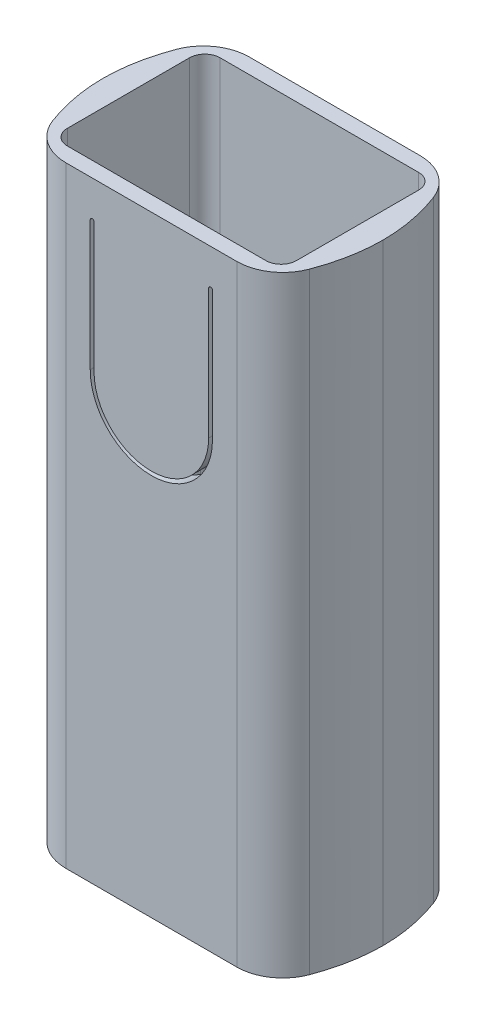
SolidWorks part; units mm, degrees
ref_plane "Front Plane" through (0, 0, 0) normal (0, 0, 1) x (1, 0, 0)
ref_plane "Top Plane" through (0, 0, 0) normal (0, 1, 0) x (1, 0, 0)
ref_plane "Right Plane" through (0, 0, 0) normal (1, 0, 0) x (0, 0, -1)
ref_plane "Plane1" through (0, 58, 0) normal (0, 1, 0) x (1, 0, 0)
sketch "Sketch8" plane through (0, 58, 0) normal (0, 1, 0) x (1, 0, 0)
  line L1 (-15, -8) -> (-15, 8)
  line L2 (-13, 10) -> (13, 10)
  line L5 (-15, 10) -> (-14.2911, 9.5274) construction
  line L8 (-11.1948, 12) -> (11.1948, 12)
  line L11 (-15.4079, 10.272) -> (-14.2911, 9.5274) construction
  line L12 (15.4079, 10.272) -> (14.2911, 9.5274) construction
  line L15 (0, 12) -> (0, -12) construction
  line L16 (15, 10) -> (14.2911, 9.5274) construction
  line L17 (15, -8) -> (15, 8)
  line L18 (15, -10) -> (14.2911, -9.5274) construction
  line L19 (15.4079, -10.272) -> (14.2911, -9.5274) construction
  line L20 (-18.3347, 0) -> (18.3347, 0) construction
  line L21 (0, 0) -> (0, 12) construction
  line L22 (-15.4079, -10.272) -> (-14.2911, -9.5274) construction
  line L23 (-15, -10) -> (-14.2911, -9.5274) construction
  line L24 (-11.1948, -12) -> (11.1948, -12)
  line L25 (-13, -10) -> (13, -10)
  arc A8 (-13, 10) -> (-15, 8) centre (-13, 8) ccw
  arc A10 (-11.1948, 12) -> (-16.8117, 8.1097) centre (-11.1948, 6) ccw
  arc A11 (11.1948, 12) -> (16.8117, 8.1097) centre (11.1948, 6) cw
  arc A12 (13, 10) -> (15, 8) centre (13, 8) cw
  arc A13 (13, -10) -> (15, -8) centre (13, -8) ccw
  arc A14 (11.1948, -12) -> (16.8117, -8.1097) centre (11.1948, -6) ccw
  arc A15 (-11.1948, -12) -> (-16.8117, -8.1097) centre (-11.1948, -6) cw
  arc A16 (-13, -10) -> (-15, -8) centre (-13, -8) cw
  spline S0 degree 3 poles (-18.3347, 0) (-18.3272, 2.7261) (-17.8195, 5.4265) (-16.8117, 8.1097) knots 0.502499 0.502499 0.502499 0.502499 0.837905 0.837905 0.837905 0.837905
  spline S1 degree 3 poles (18.3347, 0) (18.3272, 2.7261) (17.8195, 5.4265) (16.8117, 8.1097) knots 0.502499 0.502499 0.502499 0.502499 0.837905 0.837905 0.837905 0.837905
  spline S2 degree 3 poles (18.3347, 0) (18.3272, -2.7261) (17.8195, -5.4265) (16.8117, -8.1097) knots 0.502499 0.502499 0.502499 0.502499 0.837905 0.837905 0.837905 0.837905
  spline S3 degree 3 poles (-18.3347, 0) (-18.3272, -2.7261) (-17.8195, -5.4265) (-16.8117, -8.1097) knots 0.502499 0.502499 0.502499 0.502499 0.837905 0.837905 0.837905 0.837905
  point P0 (0, 0)
  point P4 (0, 0)
  point P5 (0, 0)
  point P8 (-15, 0)
  point P19 (-15, 10)
  point P26 (0, 0)
  point P27 (-12, 9.5)
  point P36 (0, 10)
  point P37 (12, 9.5)
  point P51 (-18.3347, 0)
  point P53 (-15, 0)
  point P55 (12, -9.5)
  point P61 (15, 0)
  point P62 (0, -10)
  point P63 (-12, -9.5)
  dimension "D3" = 8.2959
  dimension "D6" = 3.8903
  dimension "D2" = 6
  dimension "D7" = 2
  dimension "D1" = 13.9635
  dimension "D4" = 3.3347
  dimension "D5" = 1.523
  dimension "D8" = 2
  dimension "D9" = 15
sketch "Sketch11" plane through (0, 58, 0) normal (0, 1, 0) x (1, 0, 0)
  line L10 (-13, 10) -> (13, 10) construction
  line L11 (13, 10) -> (15, 10)
  line L13 (-13, 7.4379) -> (-13, 10)
  line L19 (15, 10) -> (15, 6.9379)
  line L20 (15, 6.9379) -> (13.5, 6.9379)
  line L21 (13, 7.4379) -> (13, 10)
  line L22 (-15, 6.9379) -> (-13.5, 6.9379)
  line L23 (-15, 10) -> (-15, 6.9379)
  line L24 (-13, 10) -> (-15, 10)
  arc A4 (13.5, 6.9379) -> (13, 7.4379) centre (13.5, 7.4379) cw
  arc A5 (-13.5, 6.9379) -> (-13, 7.4379) centre (-13.5, 7.4379) ccw
  point P14 (0, 0)
  dimension "D1" = 0.5
extrude "Boss-Extrude4" add sketch "Sketch8" along normal blind 80
extrude "Boss-Extrude5" add sketch "Sketch11" along normal blind 57
sketch "Sketch12" plane through (0, 0, 12) normal (0, 0, 1) x (1, 0, 0)
  line L1 (0, 116.1342) -> (0, 135.2209) construction
  line L2 (7.5, 133.1342) -> (7.5, 116.1342)
  line L3 (-7.5, 133.1342) -> (-7.5, 116.1342)
  line L4 (8, 133.1342) -> (8, 116.1342)
  line L5 (-8, 116.1342) -> (-8, 133.1342)
  line L6 (7.5, 130.5553) -> (0, 130.5553) construction
  line L7 (0, 130.5553) -> (-7.5, 130.5553) construction
  line L8 (-11.1948, 138) -> (11.1948, 138) construction
  line L9 (0, 138) -> (0, 58) construction
  line L10 (13.2, 58) -> (-13.2, 58) construction
  arc A1 (8, 116.1342) -> (-8, 116.1342) centre (0, 116.1342) cw
  arc A2 (7.5, 133.1342) -> (8, 133.1342) centre (7.75, 133.1342) cw
  arc A3 (-8, 133.1342) -> (-7.5, 133.1342) centre (-7.75, 133.1342) cw
  arc A4 (7.5, 116.1342) -> (-7.5, 116.1342) centre (0, 116.1342) cw
  point P1 (0, 108.6342)
  point P6 (0, 0)
  point P14 (0, 108.1342)
  point P20 (0.4953, 108.6342)
  point P23 (0, 138)
  dimension "D5" = 0.5
  dimension "D1" = 15
  dimension "D2" = 0.5
  dimension "D3" = 0.5
  dimension "D4" = 25
  dimension "D7" = 4.6657
extrude "Cut-Extrude1" cut sketch "Sketch12" against normal blind 2
